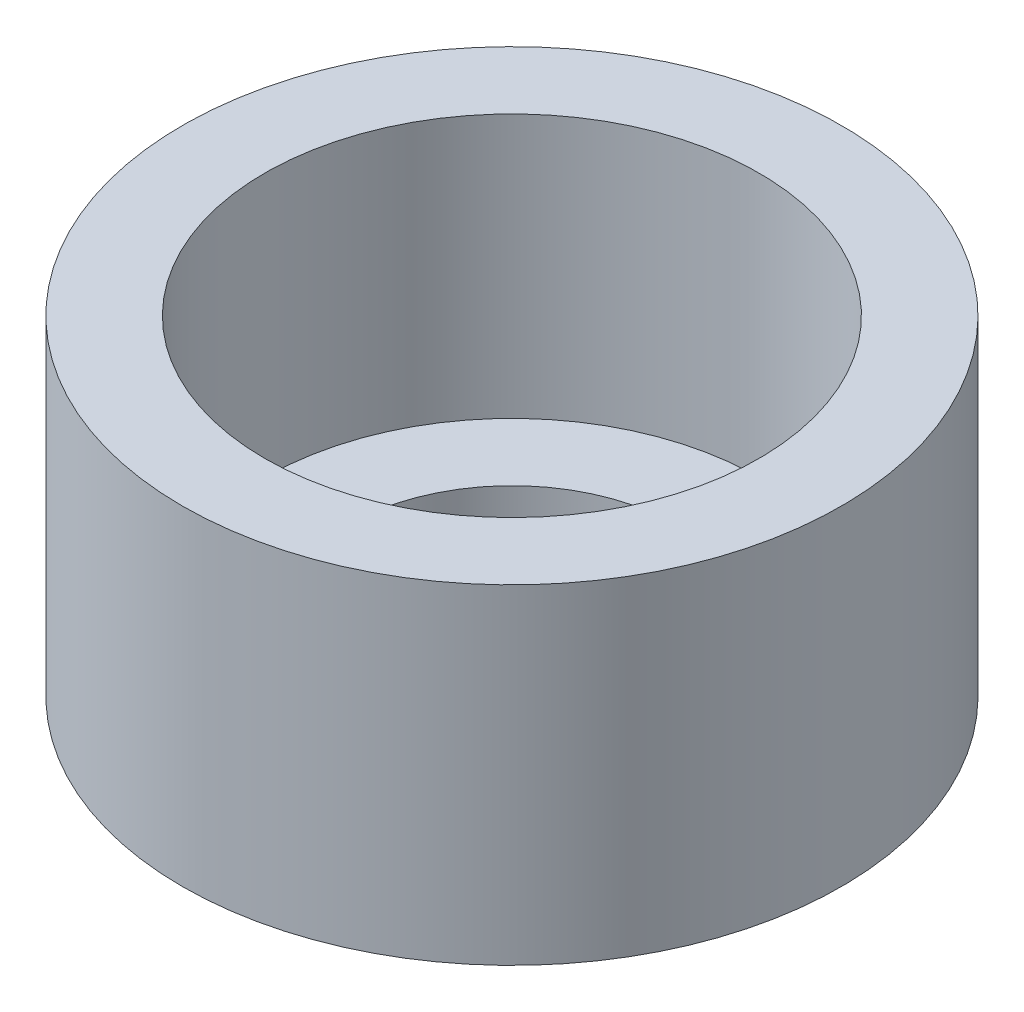
SolidWorks part; units mm, degrees
ref_plane "Front Plane" through (0, 0, 0) normal (0, 0, 1) x (1, 0, 0)
ref_plane "Top Plane" through (0, 0, 0) normal (0, 1, 0) x (1, 0, 0)
ref_plane "Right Plane" through (0, 0, 0) normal (1, 0, 0) x (0, 0, -1)
sketch "Sketch2" plane through (0, 0, 0) normal (0, 1, 0) x (1, 0, 0)
  circle A0 centre (0, 0) radius 5
  circle A1 centre (0, 0) radius 10
  dimension "D1" = 10
  dimension "D2" = 20
extrude "Boss-Extrude1" add sketch "Sketch2" along normal blind 10
sketch "Sketch3" plane through (0, 10, 0) normal (0, 1, 0) x (1, 0, 0)
  circle A0 centre (0, 0) radius 7.5
  dimension "D1" = 15
extrude "Cut-Extrude1" cut sketch "Sketch3" against normal blind 8 contours A0
